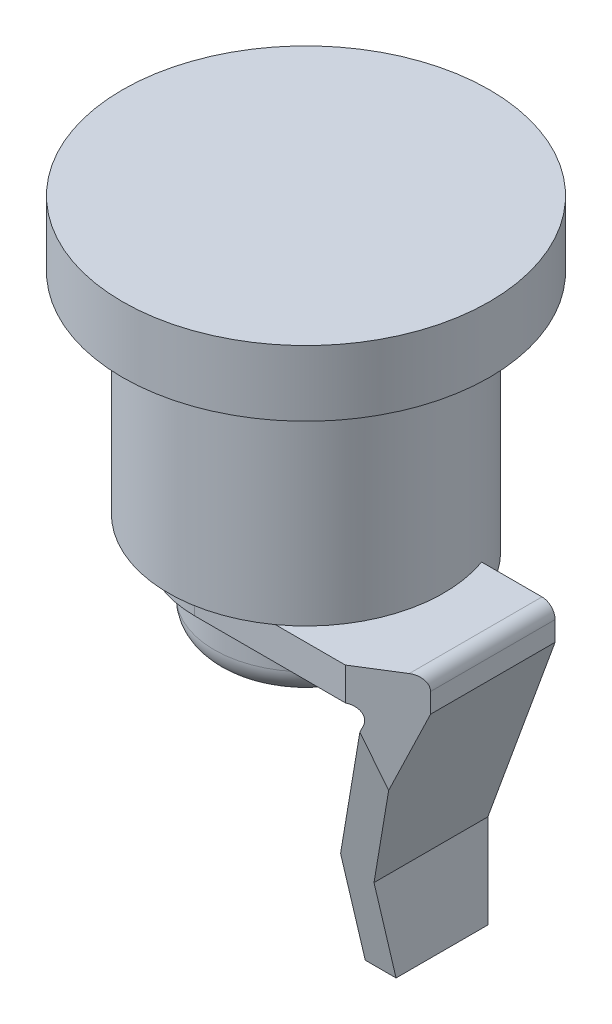
SolidWorks part; units mm, degrees
ref_plane "Front Plane" through (0, 0, 0) normal (0, 0, 1) x (1, 0, 0)
ref_plane "Top Plane" through (0, 0, 0) normal (0, 1, 0) x (1, 0, 0)
ref_plane "Right Plane" through (0, 0, 0) normal (1, 0, 0) x (0, 0, -1)
sketch "Sketch1" plane through (0, 0, 0) normal (0, 1, 0) x (1, 0, 0)
  circle A0 centre (0, 0) radius 14
  dimension "D1" = 28
extrude "Boss-Extrude1" add sketch "Sketch1" along normal blind 5
sketch "Sketch2" plane through (0, 0, 0) normal (0, -1, 0) x (1, 0, 0)
  circle A0 centre (0, 0) radius 10.5
extrude "Boss-Extrude2" add sketch "Sketch2" along normal blind 16
sketch "Sketch3" plane through (0, -16, 0) normal (0, -1, 0) x (1, 0, 0)
  circle A0 centre (0, 0) radius 8.5
extrude "Boss-Extrude3" add sketch "Sketch3" along normal blind 2.5
sketch "Sketch4" plane through (0, -18.5, 0) normal (0, -1, 0) x (1, 0, 0)
  circle A0 centre (0, 0) radius 7
extrude "Boss-Extrude4" add sketch "Sketch4" along normal blind 5
fillet "Fillet1" radius 2 1 edges at (0, -23.5, -7)
sketch "Sketch5" plane through (0, -18.5, 0) normal (0, -1, 0) x (1, 0, 0)
  line L1 (0, 8.5) -> (15.5, 8.5)
  line L2 (0, 8.5) -> (0, -8.5)
  line L3 (0, -8.5) -> (15.5, -8.5)
  line L4 (15.5, 8.5) -> (15.5, -8.5)
  circle A0 centre (0, 0) radius 8.5 construction
  circle A1 centre (0, 0) radius 8.5
  circle M7 centre (0, 0) radius 8.5
  dimension "D1" = 15.5
extrude "Boss-Extrude5" add sketch "Sketch5" against normal blind 2.5 contours L4 L1 L3 M7
sketch "Sketch7" plane through (0, 0, 8.5) normal (0, 0, 1) x (1, 0, 0)
  line L0 (15.5, -18.5) -> (10.3697, -32.5954)
  line L2 (8.0205, -31.7403) -> (12.8396, -18.5)
  line L3 (0, -18.5) -> (15.5, -18.5) construction
  line L4 (12.8396, -18.5) -> (15.5, -18.5)
  line L5 (8.0205, -31.7403) -> (8.0205, -39.7403)
  line L6 (8.0205, -39.7403) -> (10.3697, -39.7403)
  line L7 (10.3697, -39.7403) -> (10.3697, -32.5954)
  line L8 (8.0205, -31.7403) -> (10.3697, -32.5954) construction
  dimension "D1" = 2.5
  dimension "D2" = 70
  dimension "D3" = 8
  dimension "D4" = 15
extrude "Boss-Extrude7" add sketch "Sketch7" against normal up to surface (17 mm away) up to face at (7.4329, -17, -8.5)
fillet "Fillet3" radius 1 2 edges at (12.8396, -18.5, 0) (15.5, -16, 0)
sketch "Sketch8" plane through (15.5, 0, 0) normal (1, 0, 0) x (0, 0, -1)
  line L0 (-8.5, -18.5) -> (8.5, -18.5) construction
  line L1 (-8.5, -39.7403) -> (-8.5, -32.5954) construction
  line L2 (-8.5, -32.5954) -> (-8.5, -18.5) construction
  line L3 (8.5, -32.5954) -> (8.5, -18.5) construction
  line L4 (8.5, -39.7403) -> (8.5, -32.5954) construction
  line L5 (8.5, -39.7403) -> (-8.5, -39.7403) construction
  line L6 (-8.5, -18.5) -> (8.5, -18.5)
  line L7 (-8.5, -39.7403) -> (-8.5, -32.5954)
  line L8 (-8.5, -32.5954) -> (-8.5, -18.5)
  line L9 (8.5, -32.5954) -> (8.5, -18.5)
  line L10 (8.5, -39.7403) -> (8.5, -32.5954)
  line L11 (8.5, -39.7403) -> (-8.5, -39.7403)
  line L12 (8.5, -18.5) -> (3.5, -39.7403)
  line L13 (-8.5, -18.5) -> (-3.5, -39.7403)
  dimension "D1" = 5
  dimension "D2" = 5
extrude "Cut-Extrude1" cut sketch "Sketch8" against normal up to surface (7.4795 mm away) contours L13 L8 L7 L11 | L9 L12 L11 L10
sketch "Sketch9" plane through (0, -16, 0) normal (0, 1, 0) x (1, 0, 0)
  line L0 (6.1644, -8.5) -> (14.5, -8.5) construction
  line L1 (14.5, -8.5) -> (15.5, -8.5) construction
  line L2 (15.5, 8.5) -> (14.5, 8.5) construction
  line L3 (6.1644, 8.5) -> (14.5, 8.5) construction
  line L4 (15.5, 8.5) -> (15.5, -8.5) construction
  line L5 (6.1644, -8.5) -> (14.5, -8.5)
  line L6 (14.5, -8.5) -> (15.5, -8.5)
  line L7 (15.5, 8.5) -> (14.5, 8.5)
  line L8 (6.1644, 8.5) -> (14.5, 8.5)
  line L9 (15.5, 8.5) -> (15.5, -8.5)
  line L10 (11.5, 8.5) -> (15.5, 6)
  line L11 (15.5, -6) -> (11.5, -8.5)
  line L12 (11.5, 8.5) -> (11.5, -8.5) construction
  line L13 (11.5, 8.5) -> (15.5, 8.5)
  line L14 (15.5, -8.5) -> (11.5, -8.5)
  line L15 (8.0205, 3.5) -> (10.3697, 3.5) construction
  line L16 (8.0205, 3.5) -> (10.3697, 3.5)
  line L17 (9.8995, 3.5) -> (15.5, 3.5)
  arc A0 (6.1644, -8.5) -> (6.1644, 8.5) centre (0, 0) ccw construction
  arc A1 (6.1644, -8.5) -> (6.1644, 8.5) centre (0, 0) ccw
  line M3 (14.5, -8.5) -> (14.5, 8.5)
  line M4 (14.5, 8.5) -> (6.1644, 8.5)
  arc M5 (6.1644, 8.5) -> (6.1644, -8.5) centre (0, 0) cw
  dimension "D1" = 2.5
  dimension "D2" = 2.5
  dimension "D3" = 4
extrude "Cut-Extrude2" cut sketch "Sketch9" against normal blind 20 contours L10 L9 L7 M3 | L10 M4 M3 | L9 L11 L6 M3 | L11 L5 M3 | L17 L9 L10 M3 | L10 L12 L17 M3 | L12 L8 L16 L17 M5
sketch "Sketch10" plane through (10.3697, 0, 0) normal (1, 0, 0) x (0, 0, -1)
  line L1 (3.5, -39.7403) -> (12.3008, -39.7403)
  line L2 (3.5, -39.7403) -> (3.5, -23.8695)
  line L3 (3.5, -23.8695) -> (12.3008, -23.8695)
  line L4 (12.3008, -39.7403) -> (12.3008, -23.8695)
extrude "Cut-Extrude3" cut sketch "Sketch10" against normal blind 10
